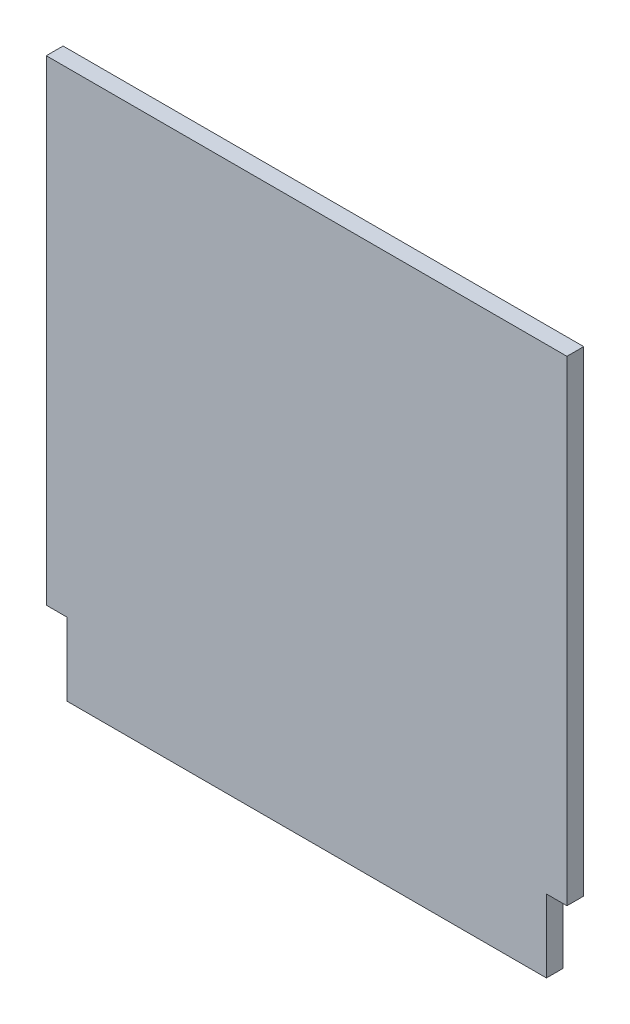
SolidWorks part; units mm, degrees
ref_plane "Front Plane" through (0, 0, 0) normal (0, 0, 1) x (1, 0, 0)
ref_plane "Top Plane" through (0, 0, 0) normal (0, 1, 0) x (1, 0, 0)
ref_plane "Right Plane" through (0, 0, 0) normal (1, 0, 0) x (0, 0, -1)
sketch "Sketch1" plane through (0, 0, 0) normal (0, 0, 1) x (1, 0, 0)
  line L1 (-46.5, 49) -> (46.5, 49)
  line L2 (-46.5, 49) -> (-46.5, -49)
  line L3 (-46.5, -49) -> (46.5, -49)
  line L4 (46.5, 49) -> (46.5, -49)
  line L5 (-46.5, 49) -> (46.5, -49) construction
  line L6 (-46.5, -49) -> (46.5, 49) construction
  point P0 (0, 0)
  dimension "D1" = 93
  dimension "D2" = 98
extrude "Boss-Extrude1" add sketch "Sketch1" along normal blind 3
sketch "Sketch2" plane through (0, 0, 3) normal (0, 0, 1) x (1, 0, 0)
  line L0 (0, 49) -> (0, -57.7374) construction
  line L1 (46.5, 49) -> (-46.5, 49) construction
  line L2 (-46.5, -36) -> (-42.8417, -36)
  line L3 (-46.5, 49) -> (-46.5, -49) construction
  line L4 (-42.8417, -36) -> (-42.8417, -49)
  line L5 (-46.5, -49) -> (46.5, -49) construction
  line L6 (-46.5, -36) -> (-46.5, -49)
  line L7 (-46.5, -49) -> (-42.8417, -49)
  line L8 (46.5, -36) -> (46.5, -49)
  line L9 (46.5, -36) -> (42.8417, -36)
  line L10 (42.8417, -36) -> (42.8417, -49)
  line L11 (46.5, -49) -> (42.8417, -49)
  dimension "D1" = 13
extrude "Cut-Extrude1" cut sketch "Sketch2" against normal blind 3
